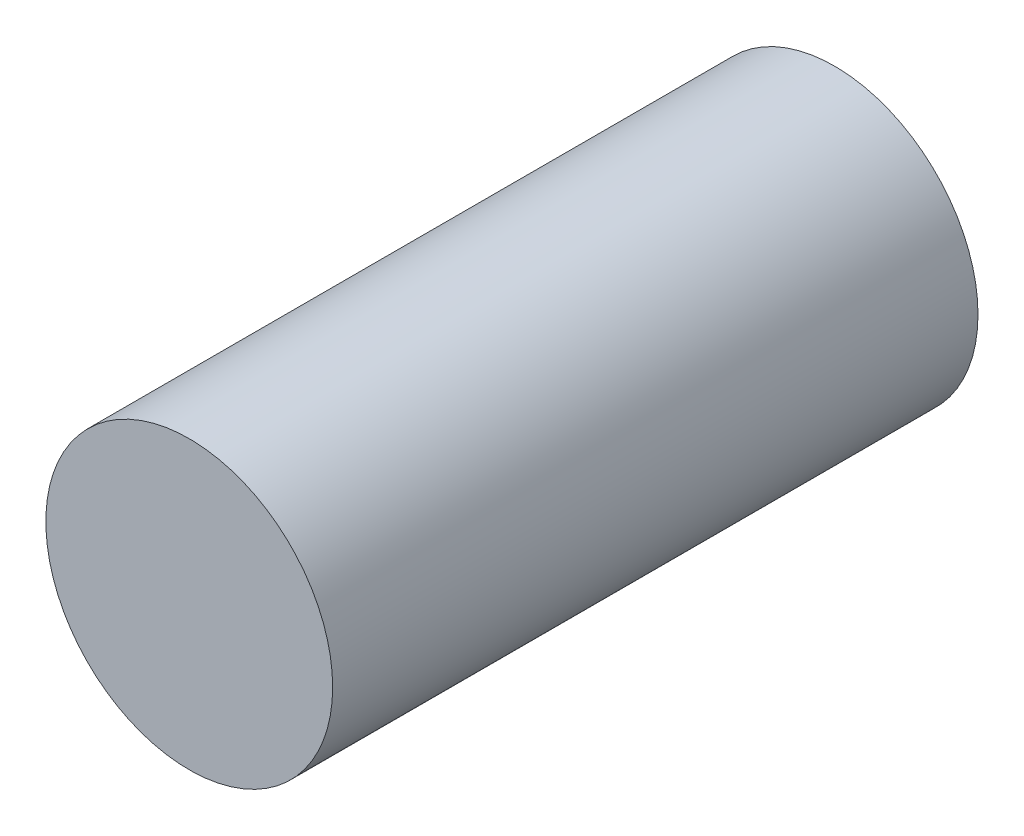
SolidWorks part; units mm, degrees
ref_plane "Front" through (0, 0, 0) normal (0, 0, 1) x (1, 0, 0)
ref_plane "Top" through (0, 0, 0) normal (0, 1, 0) x (1, 0, 0)
ref_plane "Right" through (0, 0, 0) normal (1, 0, 0) x (0, 0, -1)
sketch "草图1" plane through (0, 0, 0) normal (0, 0, 1) x (1, 0, 0)
  circle A0 centre (0, 0) radius 30
  dimension "D1" = 60
extrude "凸台-拉伸1" add sketch "草图1" along normal blind 135
